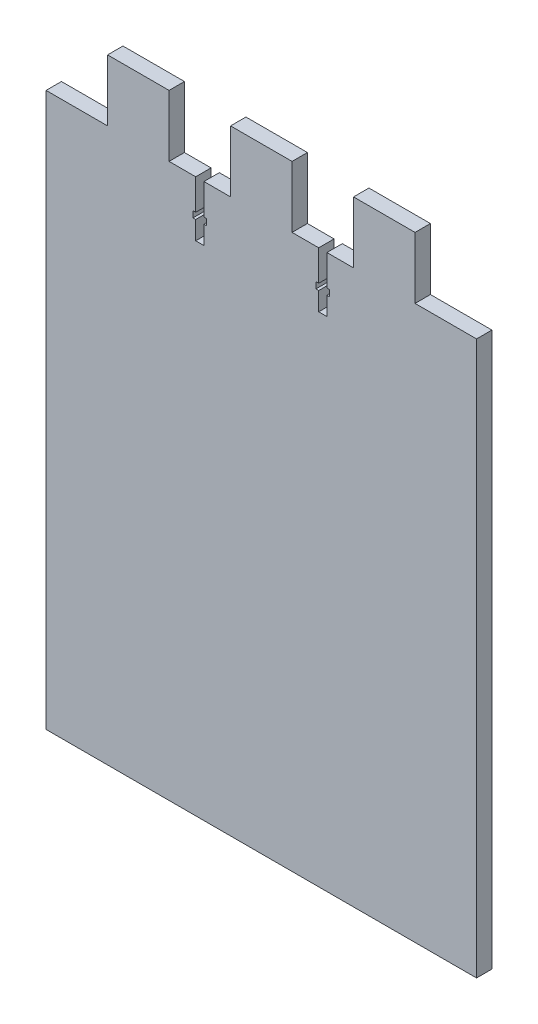
SolidWorks part; units mm, degrees
ref_plane "Front Plane" through (0, 0, 0) normal (0, 0, 1) x (1, 0, 0)
ref_plane "Top Plane" through (0, 0, 0) normal (0, 1, 0) x (1, 0, 0)
ref_plane "Right Plane" through (0, 0, 0) normal (1, 0, 0) x (0, 0, -1)
sketch "Sketch1" plane through (0, 0, 0) normal (0, 0, 1) x (1, 0, 0)
  line L0 (0, 0) -> (0, 228.6)
  line L1 (0, 228.6) -> (177.8, 228.6)
  line L2 (177.8, 228.6) -> (177.8, 0)
  line L3 (177.8, 0) -> (0, 0)
  line L4 (25.4, 228.6) -> (25.4, 254)
  line L5 (25.4, 254) -> (50.8, 254)
  line L6 (50.8, 254) -> (50.8, 228.6)
  line L7 (50.8, 228.6) -> (61.7982, 228.6)
  line L8 (61.7982, 228.6) -> (61.7982, 215.9)
  line L9 (61.7982, 215.9) -> (60.6552, 215.9)
  line L10 (60.6552, 215.9) -> (60.6552, 213.3092)
  line L11 (60.6552, 213.3092) -> (61.7982, 213.3092)
  line L12 (61.7982, 213.3092) -> (61.7982, 205.6892)
  line L13 (61.7982, 205.6892) -> (65.2018, 205.6892)
  line L14 (65.2018, 205.6892) -> (65.2018, 213.3092)
  line L15 (65.2018, 213.3092) -> (66.3448, 213.3092)
  line L16 (66.3448, 213.3092) -> (66.3448, 215.9)
  line L17 (66.3448, 215.9) -> (65.2018, 215.9)
  line L18 (65.2018, 215.9) -> (65.2018, 228.6)
  line L19 (63.5, 205.6892) -> (63.5, 228.6) construction
  line L20 (76.2, 228.6) -> (76.2, 254)
  line L21 (76.2, 254) -> (101.6, 254)
  line L22 (101.6, 254) -> (101.6, 228.6)
  line L23 (127, 228.6) -> (127, 254)
  line L24 (127, 254) -> (152.4, 254)
  line L25 (152.4, 254) -> (152.4, 228.6)
  line L26 (88.9, 254) -> (88.9, 228.6) construction
  line L27 (112.5982, 215.9) -> (112.5982, 228.6)
  line L28 (111.4552, 215.9) -> (112.5982, 215.9)
  line L29 (116.0018, 205.6892) -> (112.5982, 205.6892)
  line L30 (111.4552, 213.3092) -> (111.4552, 215.9)
  line L31 (112.5982, 213.3092) -> (111.4552, 213.3092)
  line L32 (112.5982, 205.6892) -> (112.5982, 213.3092)
  line L33 (117.1448, 213.3092) -> (116.0018, 213.3092)
  line L34 (116.0018, 213.3092) -> (116.0018, 205.6892)
  line L35 (117.1448, 215.9) -> (117.1448, 213.3092)
  line L36 (116.0018, 215.9) -> (117.1448, 215.9)
  line L37 (116.0018, 228.6) -> (116.0018, 215.9)
  point P30 (0, 0)
  dimension "D1" = 177.8
  dimension "D2" = 2.5908
  dimension "D3" = 3.4036
  dimension "D4" = 3.4036
  dimension "D5" = 1.143
  dimension "D6" = 12.7
  dimension "D7" = 25.4
  dimension "D8" = 7.62
  dimension "D9" = 7.62
  dimension "D10" = 10.9982
  dimension "D11" = 25.4
  dimension "D12" = 25.4
  dimension "D13" = 25.4
  dimension "D14" = 25.4
  dimension "D15" = 25.4
  dimension "D16" = 25.4
  dimension "D17" = 25.4
  dimension "D18" = 25.4
  dimension "D19" = 228.6
  dimension "D20" = 1.143
  dimension "D21" = 12.7
  dimension "D22" = 25.4
  dimension "D23" = 90
extrude "Boss-Extrude1" add sketch "Sketch1" along normal blind 6.35 contours L6 L5 L4 L1 | L22 L21 L20 L1 | L25 L24 L23 L1 | L1 L37 L36 L35 L33 L34 L29 L32 L31 L30 L28 L27 L18 L17 L16 L15 L14 L13 L12 L11 L10 L9 L8 L0 L3 L2
